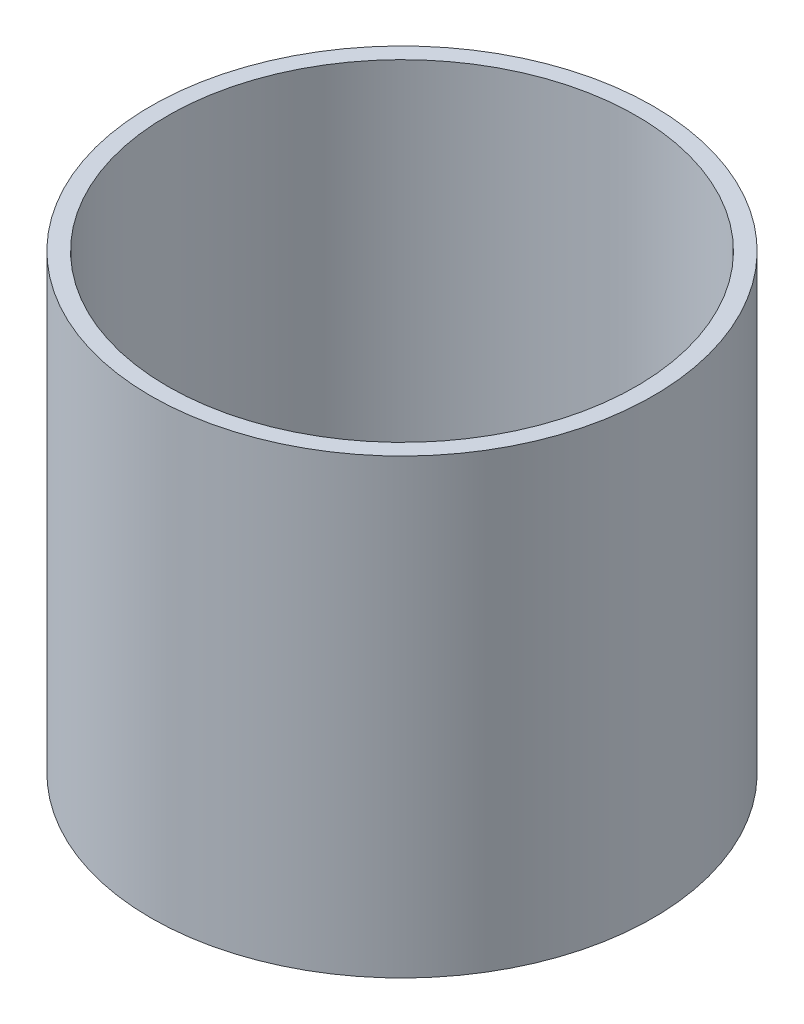
SolidWorks part; units mm, degrees
material "AISI 1045 Steel, cold drawn"
ref_plane "Front Plane" through (0, 0, 0) normal (0, 0, 1) x (1, 0, 0)
ref_plane "Top Plane" through (0, 0, 0) normal (0, 1, 0) x (1, 0, 0)
ref_plane "Right Plane" through (0, 0, 0) normal (1, 0, 0) x (0, 0, -1)
sketch "Sketch1" plane through (0, 0, 0) normal (0, 1, 0) x (1, 0, 0)
  circle A0 centre (0, 0) radius 22.5
  circle A1 centre (0, 0) radius 21
extrude "Boss-Extrude1" add sketch "Sketch1" along normal blind 35.5
sketch "Sketch2" plane through (0, 0, 0) normal (0, -1, 0) x (1, 0, 0)
  circle A0 centre (0, 0) radius 22.5
extrude "Boss-Extrude2" add sketch "Sketch2" along normal blind 5
